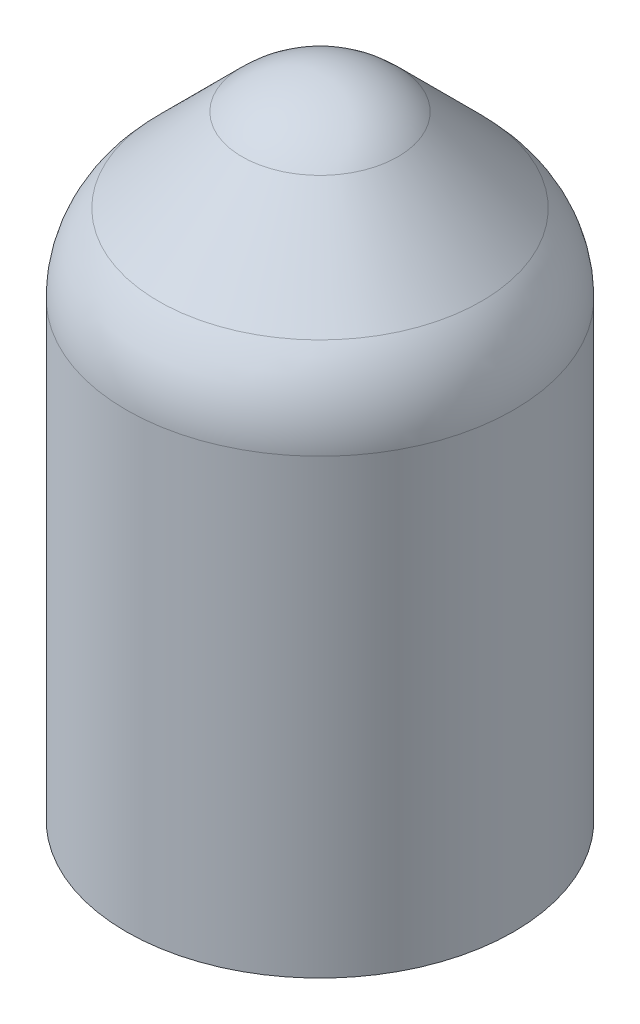
SolidWorks part; units mm, degrees
ref_plane "Front Plane" through (0, 0, 0) normal (0, 0, 1) x (1, 0, 0)
ref_plane "Top Plane" through (0, 0, 0) normal (0, 1, 0) x (1, 0, 0)
ref_plane "Right Plane" through (0, 0, 0) normal (1, 0, 0) x (0, 0, -1)
sketch "Sketch1" plane through (0, 0, 0) normal (0, 0, 1) x (1, 0, 0)
  line L1 (50, 164.1421) -> (24.1421, 190)
  line L2 (0, 200) -> (0, 140)
  line L3 (60, 140) -> (60, 0)
  line L4 (60, 0) -> (0, 0)
  line L5 (0, 0) -> (0, 140)
  arc A0 (60, 140) -> (50, 164.1421) centre (25.8579, 140) ccw
  arc A1 (24.1421, 190) -> (0, 200) centre (0, 165.8579) ccw
  point P4 (0, 0)
  dimension "D5" = 10
  dimension "D1" = 60
  dimension "D2" = 140
  dimension "D3" = 140
  dimension "D4" = 60
  dimension "D6" = 10
revolve "Revolve1" add sketch "Sketch1" angle 360 about L5
shell "Shell1" thickness 2
